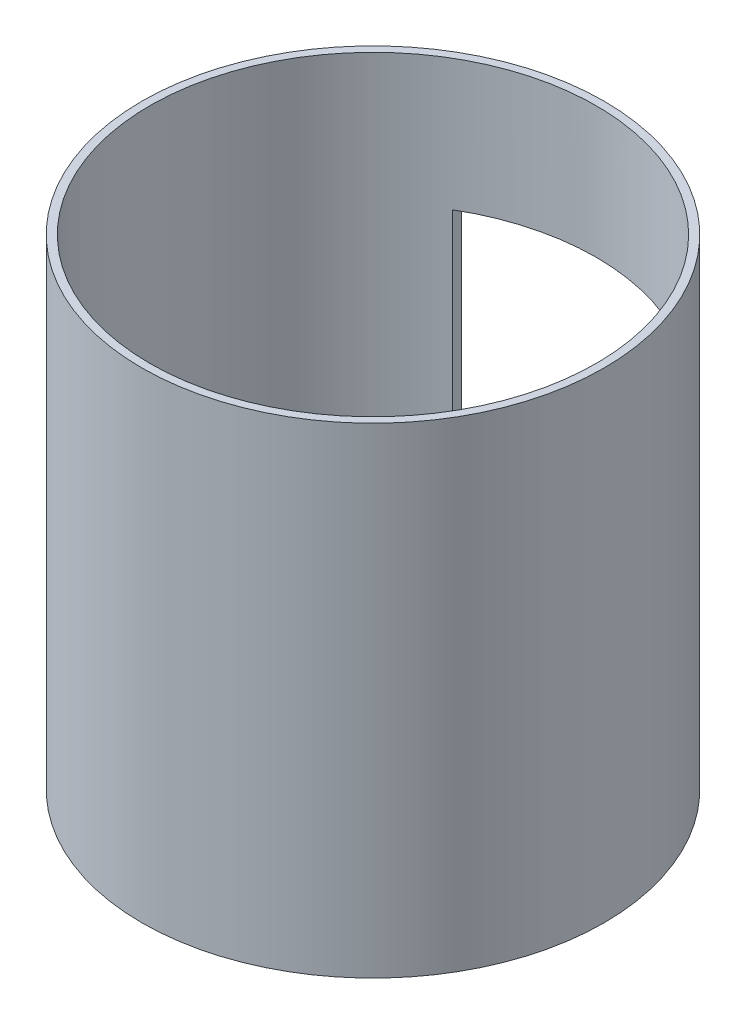
SolidWorks part; units mm, degrees
ref_plane "前视基准面" through (0, 0, 0) normal (0, 0, 1) x (1, 0, 0)
ref_plane "上视基准面" through (0, 0, 0) normal (0, 1, 0) x (1, 0, 0)
ref_plane "右视基准面" through (0, 0, 0) normal (1, 0, 0) x (0, 0, -1)
sketch "草图1" plane through (0, 0, 0) normal (0, 1, 0) x (1, 0, 0)
  circle A0 centre (0, 0) radius 85
extrude "凸台-拉伸1" add sketch "草图1" along normal blind 180
shell "抽壳1" thickness 3
sketch "草图2" plane through (0, 0, 0) normal (0, 0, 1) x (1, 0, 0)
  line L0 (-88, 180) -> (-88, -3) construction
  line L1 (88, -3) -> (88, 180) construction
  line L2 (-43, 20) -> (43, 20)
  line L3 (43, 20) -> (43, 130)
  line L4 (43, 130) -> (-43, 130)
  line L5 (-43, 130) -> (-43, 20)
  point P0 (-88, 130)
  point P1 (-88, 20)
  point P5 (-43, 130)
  point P6 (88, 130)
  point P7 (43, 130)
  dimension "D1" = 50
  dimension "D2" = 110
  dimension "D3" = 45
  dimension "D4" = 45
extrude "切除-拉伸1" cut sketch "草图2" against normal blind 180
sketch "草图3" plane through (0, 0, 0) normal (0, 1, 0) x (1, 0, 0)
  line L0 (0, 25) -> (25, 25)
  line L1 (25, 25) -> (25, -25)
  line L2 (25, -25) -> (-25, -25)
  line L3 (-25, -25) -> (-25, 25)
  line L4 (-25, 25) -> (0, 25)
  line L6 (-23.5, 23.5) -> (23.5, 23.5)
  line L7 (-23.5, 23.5) -> (-23.5, -23.5)
  line L8 (-23.5, -23.5) -> (23.5, -23.5)
  line L9 (23.5, 23.5) -> (23.5, -23.5)
  line L10 (-23.5, 23.5) -> (23.5, -23.5) construction
  line L11 (-23.5, -23.5) -> (23.5, 23.5) construction
  point P0 (0, 25)
  point P7 (0, 0)
  dimension "D1" = 25
extrude "凸台-拉伸2" add sketch "草图3" along normal blind 40
ref_plane "基准面4" through (25, 0, 0) normal (1, 0, 0) x (0, 0, -1)
sketch "草图4" plane through (25, 0, 0) normal (1, 0, 0) x (0, 0, -1)
  line L0 (-27.5927, -1.7935) -> (27.4252, -1.7935)
  line L1 (27.4252, -1.7935) -> (27.4252, 10.2065)
  line L2 (27.4252, 10.2065) -> (-27.5927, 10.2065)
  line L3 (-27.5927, 10.2065) -> (-27.5927, -1.7935)
extrude "切除-拉伸3" cut sketch "草图4" against normal blind 3
